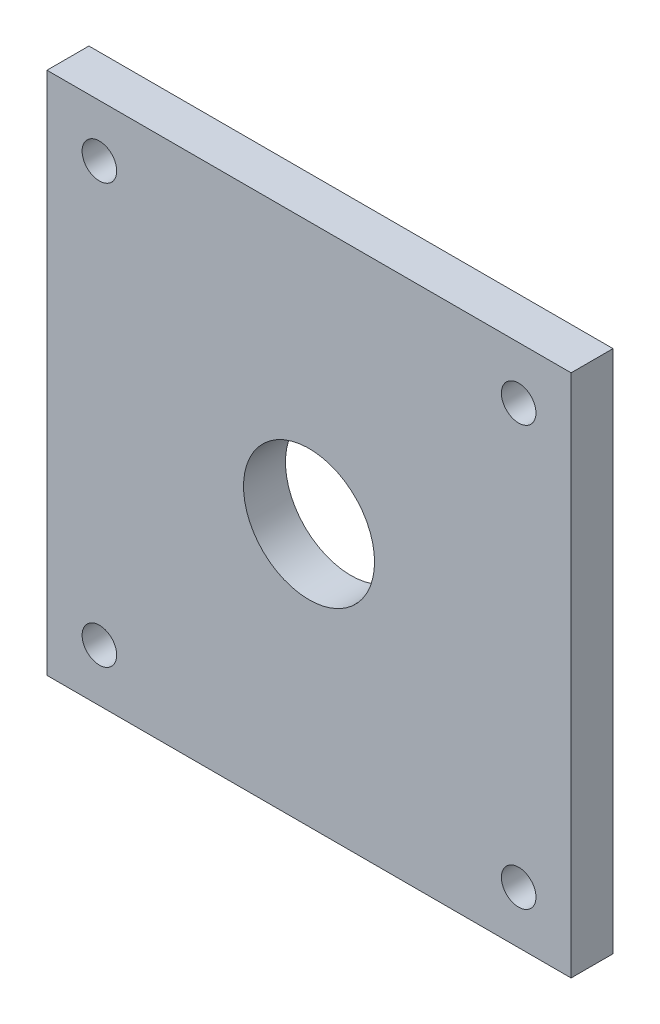
SolidWorks part; units mm, degrees
ref_plane "前视基准面" through (0, 0, 0) normal (0, 0, 1) x (1, 0, 0)
ref_plane "上视基准面" through (0, 0, 0) normal (0, 1, 0) x (1, 0, 0)
ref_plane "右视基准面" through (0, 0, 0) normal (1, 0, 0) x (0, 0, -1)
sketch "草图1" plane through (0, 0, 0) normal (0, 0, 1) x (1, 0, 0)
  line L1 (-25, -25) -> (25, -25)
  line L2 (-25, -25) -> (-25, 25)
  line L3 (-25, 25) -> (25, 25)
  line L4 (25, -25) -> (25, 25)
  line L5 (-25, -25) -> (25, 25) construction
  line L6 (-25, 25) -> (25, -25) construction
  circle A0 centre (-20, -20) radius 1.65
  circle A1 centre (-20, 20) radius 1.65
  circle A2 centre (20, 20) radius 1.65
  circle A3 centre (20, -20) radius 1.65
  circle A4 centre (0, 0) radius 6.25
  point P0 (0, 0)
  point P17 (0, 0)
  dimension "D3" = 3.3
  dimension "D6" = 12.5
  dimension "D1" = 50
  dimension "D2" = 50
  dimension "D4" = 5
  dimension "D5" = 4
extrude "凸台-拉伸1" add sketch "草图1" along normal blind 4
